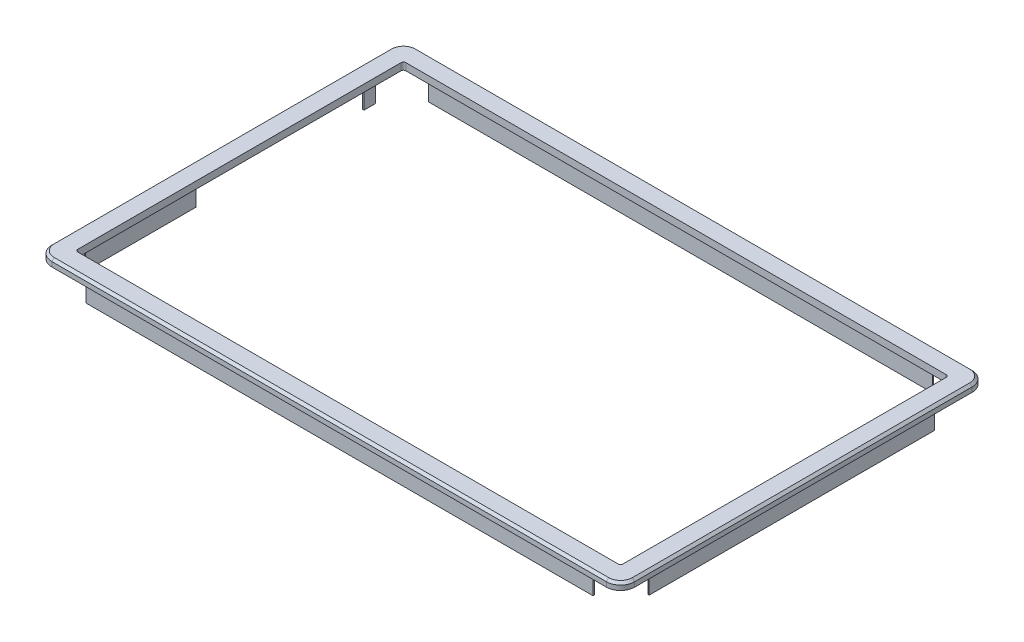
SolidWorks part; units mm, degrees
ref_plane "前视基准面" through (0, 0, 0) normal (0, 0, 1) x (1, 0, 0)
ref_plane "上视基准面" through (0, 0, 0) normal (0, 1, 0) x (1, 0, 0)
ref_plane "右视基准面" through (0, 0, 0) normal (1, 0, 0) x (0, 0, -1)
other "Configuration Table"
sketch "草图1" plane through (0, 0, 0) normal (0, 1, 0) x (1, 0, 0)
  line L1 (-117.5, 147) -> (117.5, 147)
  line L2 (-119.5, 145) -> (-119.5, 2)
  line L3 (-117.5, 0) -> (117.5, 0)
  line L4 (119.5, 145) -> (119.5, 2)
  arc A0 (117.5, 0) -> (119.5, 2) centre (117.5, 2) ccw
  arc A1 (117.5, 147) -> (119.5, 145) centre (117.5, 145) cw
  arc A2 (-119.5, 2) -> (-117.5, 0) centre (-117.5, 2) ccw
  arc A3 (-117.5, 147) -> (-119.5, 145) centre (-117.5, 145) ccw
  point P4 (0, 0)
  dimension "D1" = 2
  dimension "D2" = 239
  dimension "D3" = 147
extrude "拉伸-薄壁1" add sketch "草图1" along normal blind 10 thin
sketch "草图2" plane through (0, 10, 0) normal (0, 1, 0) x (1, 0, 0)
  line L25 (-117.5, 0) -> (117.5, 0) construction
  line L26 (-115.5, 143) -> (115.5, 143)
  line L27 (-115.5, 143) -> (-115.5, 4)
  line L28 (-115.5, 4) -> (115.5, 4)
  line L29 (123.5, 2) -> (123.5, 145)
  line L30 (-117.5, -4) -> (117.5, -4)
  line L31 (117.5, 151) -> (-117.5, 151)
  line L32 (-123.5, 145) -> (-123.5, 2)
  line L33 (123.5, 2) -> (123.5, 145)
  line L34 (-117.5, -4) -> (117.5, -4)
  line L35 (117.5, 151) -> (-117.5, 151)
  line L36 (-123.5, 145) -> (-123.5, 2)
  line L37 (115.5, 143) -> (115.5, 4)
  line L38 (117.5, 147) -> (-117.5, 147) construction
  line L39 (-119.5, 145) -> (-119.5, 2) construction
  arc A20 (123.5, 145) -> (117.5, 151) centre (117.5, 145) ccw
  arc A21 (117.5, -4) -> (123.5, 2) centre (117.5, 2) ccw
  arc A22 (-123.5, 2) -> (-117.5, -4) centre (-117.5, 2) ccw
  arc A23 (-117.5, 151) -> (-123.5, 145) centre (-117.5, 145) ccw
  arc A24 (123.5, 145) -> (117.5, 151) centre (117.5, 145) ccw
  arc A25 (117.5, -4) -> (123.5, 2) centre (117.5, 2) ccw
  arc A26 (-123.5, 2) -> (-117.5, -4) centre (-117.5, 2) ccw
  arc A27 (-117.5, 151) -> (-123.5, 145) centre (-117.5, 145) ccw
  point P4 (0, 4)
  dimension "D2" = 4
  dimension "D3" = 4
  dimension "D4" = 4
  dimension "D1" = 4
extrude "凸台-拉伸1" add sketch "草图2" along normal blind 3
fillet "圆角1" radius 1 4 edges at (115.5, 11.5, -4) (-115.5, 11.5, -4) (115.5, 11.5, -143) (-115.5, 11.5, -143)
chamfer "倒角1" distance 1 angle 45 8 edges at (123.5, 13, -73.5) (121.7426, 13, 2.2426) (0, 13, 4) (-121.7426, 13, 2.2426) (121.7426, 13, -149.2426) (0, 13, -151) (-121.7426, 13, -149.2426) (-123.5, 13, -73.5)
sketch "草图3" plane through (-119.5, 0, 0) normal (-1, 0, 0) x (0, 0, 1)
  line L0 (-145, 0) -> (-2, 0) construction
  line L1 (-129.6866, 0) -> (-58.5989, 0)
  line L2 (-129.6866, 0) -> (-129.6866, 10)
  line L3 (-129.6866, 10) -> (-58.5989, 10)
  line L4 (-58.5989, 0) -> (-58.5989, 10)
  line L5 (-145, 10) -> (-2, 10) construction
  point P6 (-58.5989, 10)
extrude "切除-拉伸1" cut sketch "草图3" against normal blind 2 and the other way through all
sketch "草图4" plane through (0, 0, 0) normal (0, -1, 0) x (1, 0, 0)
  line L1 (-128.6245, 6.0883) -> (-107.0332, 6.0883)
  line L2 (-128.6245, 6.0883) -> (-128.6245, -11.7632)
  line L3 (-128.6245, -11.7632) -> (-107.0332, -11.7632)
  line L4 (-107.0332, 6.0883) -> (-107.0332, -11.7632)
  line L5 (-128.6245, -150.6241) -> (-108.3526, -150.6241)
  line L6 (-128.6245, -150.6241) -> (-128.6245, -134.4712)
  line L7 (-128.6245, -134.4712) -> (-108.3526, -134.4712)
  line L8 (-108.3526, -150.6241) -> (-108.3526, -134.4712)
  line L9 (105.2083, -132.9633) -> (125.534, -132.9633)
  line L10 (105.2083, -132.9633) -> (105.2083, -152.5989)
  line L11 (105.2083, -152.5989) -> (125.534, -152.5989)
  line L12 (125.534, -132.9633) -> (125.534, -152.5989)
  line L13 (107.8472, -12.1402) -> (130.004, -12.1402)
  line L14 (107.8472, -12.1402) -> (107.8472, 16.7315)
  line L15 (107.8472, 16.7315) -> (130.004, 16.7315)
  line L16 (130.004, -12.1402) -> (130.004, 16.7315)
  point P19 (-107.0332, -11.7632)
  point P20 (0, 0)
  point P21 (107.8472, -12.1402)
  point P22 (0, 0)
  point P23 (105.2083, -132.9633)
  point P24 (0, 0)
  point P25 (-108.3526, -134.4712)
extrude "切除-拉伸2" cut sketch "草图4" against normal up to surface (10 mm away) up to face at (-23.84, 10, -77.6285)
